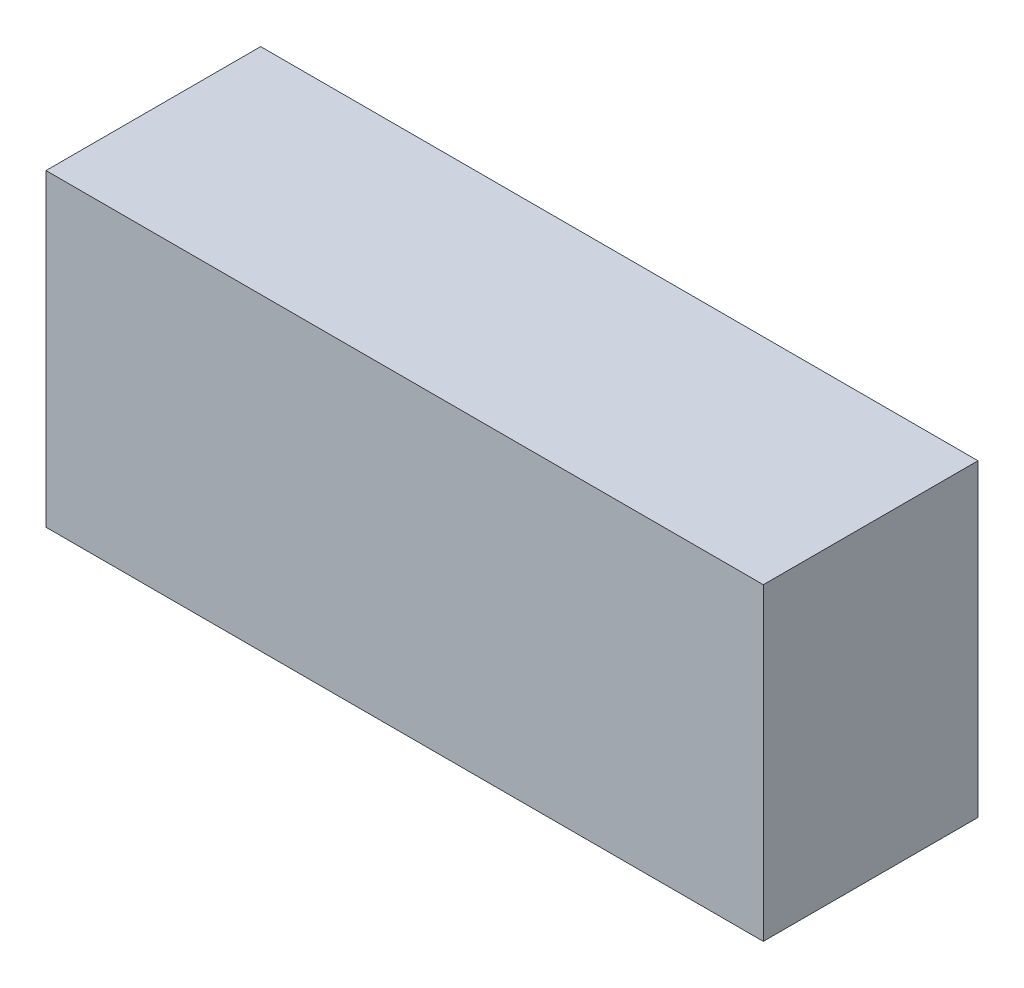
SolidWorks part; units mm, degrees
ref_plane "前视基准面" through (0, 0, 0) normal (0, 0, 1) x (1, 0, 0)
ref_plane "上视基准面" through (0, 0, 0) normal (0, 1, 0) x (1, 0, 0)
ref_plane "右视基准面" through (0, 0, 0) normal (1, 0, 0) x (0, 0, -1)
sketch "草图1" plane through (0, 0, 0) normal (0, 1, 0) x (1, 0, 0)
  line L1 (-68.5, -20.5) -> (68.5, -20.5)
  line L2 (-68.5, -20.5) -> (-68.5, 20.5)
  line L3 (-68.5, 20.5) -> (68.5, 20.5)
  line L4 (68.5, -20.5) -> (68.5, 20.5)
  line L5 (-68.5, -20.5) -> (68.5, 20.5) construction
  line L6 (-68.5, 20.5) -> (68.5, -20.5) construction
  point P0 (0, 0)
  dimension "D1" = 137
  dimension "D2" = 41
extrude "凸台-拉伸1" add sketch "草图1" along normal blind 59
